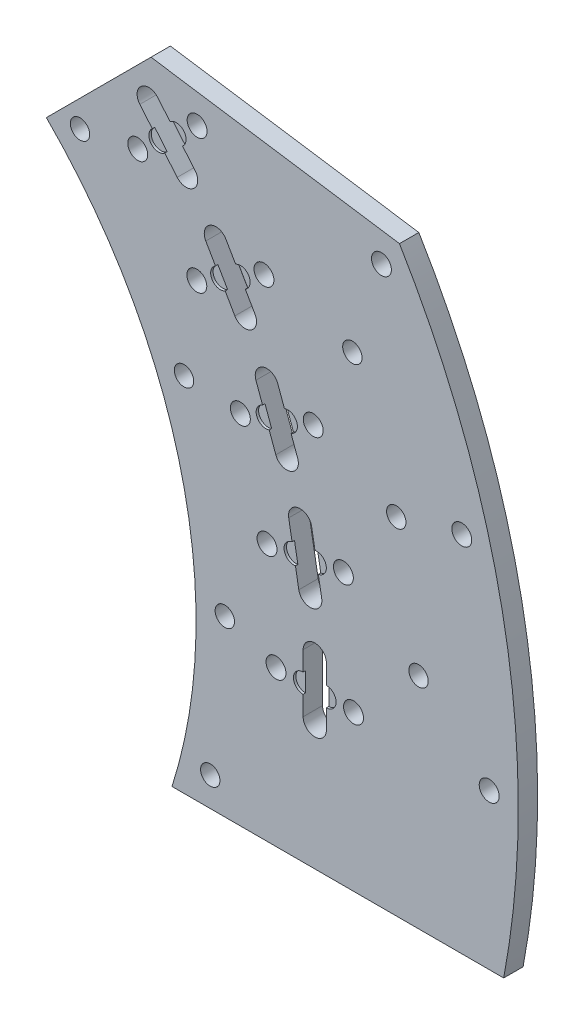
SolidWorks part; units mm, degrees
ref_plane "Front Plane" through (0, 0, 0) normal (0, 0, 1) x (1, 0, 0)
ref_plane "Top Plane" through (0, 0, 0) normal (0, 1, 0) x (1, 0, 0)
ref_plane "Right Plane" through (0, 0, 0) normal (1, 0, 0) x (0, 0, -1)
sketch "Sketch1" plane through (0, 0, 0) normal (0, 0, 1) x (1, 0, 0)
  line L0 (0, 0) -> (177.8, 0) construction
  line L1 (176.8984, 6.1774) -> (0, 0) construction
  line L2 (0, 0) -> (121.7947, 121.7947) construction
  line L3 (121.7947, 121.7947) -> (122.9173, 122.9173) construction
  line L4 (129.4542, 120.718) -> (0, 0) construction
  line L5 (0, 0) -> (163.5325, 67.7374) construction
  line L6 (167.4812, 0) -> (167.4812, -50.8) construction
  line L8 (159.5911, -50.8) -> (167.4812, -50.8) construction
  line L9 (172.1267, -41.275) -> (0, 0) construction
  line L10 (159.5911, -50.8) -> (268.2828, -50.8)
  line L11 (118.4271, 118.4271) -> (152.7152, 152.7152)
  line L12 (177.8, 0) -> (193.675, 0) construction
  line L13 (202.565, 0) -> (210.185, 0) construction
  line L14 (210.185, 0) -> (219.075, 0) construction
  line L15 (193.675, 0) -> (202.565, 0) construction
  line L16 (202.565, 0) -> (202.565, 9.525)
  line L17 (202.565, 0) -> (202.565, -9.525)
  line L18 (210.185, 9.525) -> (210.185, 0)
  line L19 (210.185, 0) -> (210.185, -9.525)
  line L20 (202.565, -9.525) -> (210.185, -9.525) construction
  line L21 (202.565, 9.525) -> (210.185, 9.525) construction
  line L22 (210.185, 9.525) -> (219.075, 0) construction
  line L23 (202.565, 9.525) -> (193.675, 0) construction
  line L24 (199.4876, 35.175) -> (201.1416, 25.7947)
  line L25 (199.4876, 35.175) -> (197.8336, 44.5553)
  line L26 (205.3378, 45.8785) -> (206.9918, 36.4982)
  line L27 (206.9918, 36.4982) -> (208.6458, 27.1179)
  line L28 (190.3488, 69.2813) -> (193.6066, 60.3307)
  line L29 (190.3488, 69.2813) -> (187.0911, 78.2319)
  line L30 (194.2516, 80.8381) -> (197.5093, 71.8875)
  line L31 (197.5093, 71.8875) -> (200.767, 62.9369)
  line L32 (175.4264, 101.2825) -> (180.1889, 93.0336)
  line L33 (175.4264, 101.2825) -> (170.6639, 109.5314)
  line L34 (177.263, 113.3414) -> (182.0255, 105.0925)
  line L35 (182.0255, 105.0925) -> (186.788, 96.8436)
  line L36 (155.1738, 130.2063) -> (161.2963, 122.9097)
  line L37 (155.1738, 130.2063) -> (149.0512, 137.5028)
  line L38 (154.8885, 142.4009) -> (161.0111, 135.1043)
  line L39 (161.0111, 135.1043) -> (167.1336, 127.8077)
  line L40 (0, 0) -> (193.675, 0) construction
  line L41 (0, 0) -> (190.7326, 33.6313) construction
  line L42 (0, 0) -> (254, 0) construction
  line L43 (254, 0) -> (263.525, 0) construction
  line L44 (254.5456, 68.2053) -> (0, 0) construction
  line L45 (152.7152, 152.7152) -> (234.123, 140.5088)
  line L46 (167.8212, 140.8187) -> (228.2193, 131.7625) construction
  line L47 (254.5456, 68.2053) -> (263.746, 70.6705) construction
  line L48 (0, 0) -> (240.3818, 21.0307) construction
  line L49 (0, 0) -> (240.3818, 21.0307) construction
  line L50 (0, 0) -> (233.0779, 62.453) construction
  arc A0 (172.2437, 0) -> (121.7947, 121.7947) centre (0, 0) ccw construction
  arc A1 (173.8312, 0) -> (122.9173, 122.9173) centre (0, 0) ccw construction
  circle A2 centre (176.8984, 6.1774) radius 3.175
  circle A3 centre (129.4542, 120.718) radius 3.175
  circle A4 centre (163.5325, 67.7374) radius 3.175
  arc A5 (167.4812, 0) -> (118.4271, 118.4271) centre (0, 0) ccw
  arc A6 (167.4812, 0) -> (159.5911, -50.8) centre (0, 0) cw
  arc A7 (173.8312, 0) -> (166.2428, -50.8) centre (0, 0) cw construction
  circle A8 centre (172.1267, -41.275) radius 3.175
  circle A9 centre (193.675, 0) radius 9.525 construction
  circle A10 centre (219.075, 0) radius 9.525 construction
  arc A11 (202.565, -9.525) -> (210.185, -9.525) centre (206.375, -9.525) ccw
  arc A12 (202.565, 9.525) -> (210.185, 9.525) centre (206.375, 9.525) cw
  circle A13 centre (193.675, 0) radius 3.2639
  circle A14 centre (219.075, 0) radius 3.2639
  circle A15 centre (215.7468, 38.042) radius 3.2639
  arc A16 (201.1416, 25.7947) -> (208.6458, 27.1179) centre (204.8937, 26.4563) ccw
  arc A17 (197.8336, 44.5553) -> (205.3378, 45.8785) centre (201.5857, 45.2169) cw
  circle A18 centre (190.7326, 33.6313) radius 3.2639
  circle A19 centre (205.8632, 74.9281) radius 3.2639
  arc A20 (193.6066, 60.3307) -> (200.767, 62.9369) centre (197.1868, 61.6338) ccw
  arc A21 (187.0911, 78.2319) -> (194.2516, 80.8381) centre (190.6713, 79.535) cw
  circle A22 centre (181.995, 66.2408) radius 3.2639
  circle A23 centre (189.7245, 109.5375) radius 3.2639
  arc A24 (180.1889, 93.0336) -> (186.788, 96.8436) centre (183.4885, 94.9386) ccw
  arc A25 (170.6639, 109.5314) -> (177.263, 113.3414) centre (173.9635, 111.4364) cw
  circle A26 centre (167.7275, 96.8375) radius 3.2639
  circle A27 centre (167.8212, 140.8187) radius 3.2639
  arc A28 (161.2963, 122.9097) -> (167.1336, 127.8077) centre (164.215, 125.3587) ccw
  arc A29 (149.0512, 137.5028) -> (154.8885, 142.4009) centre (151.9699, 139.9519) cw
  circle A30 centre (148.3637, 124.4919) radius 3.2639
  circle A31 centre (263.525, 0) radius 3.2639
  circle A32 centre (254.5456, 68.2053) radius 3.2639
  circle A33 centre (228.2193, 131.7625) radius 3.2639
  arc A34 (234.123, 140.5088) -> (268.2828, -50.8) centre (0, 0) cw
  circle A36 centre (240.3818, 21.0307) radius 3.175
  circle A37 centre (233.0779, 62.453) radius 3.175
  circle A38 centre (218.6921, 101.9778) radius 3.175
  point P3 (172.2437, 0)
  point P96 (0, 0)
  point P97 (223.9759, 105.0925)
  point P100 (-0.8179, 0)
  dimension "D3" = 1.5875
  dimension "D4" = 6.35
  dimension "D5" = 2
  dimension "D7" = 2
  dimension "D8" = 6.35
  dimension "D9" = 6.35
  dimension "D11" = 6.35
  dimension "D13" = 6.35
  dimension "D15" = 19.05
  dimension "D16" = 7.62
  dimension "D17" = 19.05
  dimension "D21" = 15.875
  dimension "D22" = 6.5278
  dimension "D23" = 6.5278
  dimension "D28" = 6.5278
  dimension "D32" = 9.525
  dimension "D33" = 5
  dimension "D34" = 241.3
  dimension "D35" = 6.35
  dimension "D1" = 177.8
  dimension "D2" = 5.5562
  dimension "D6" = 45
  dimension "D10" = 22.5
  dimension "D12" = 50.8
  dimension "D14" = 9.525
  dimension "D18" = 9.525
  dimension "D19" = 9.525
  dimension "D20" = 25.4
  dimension "D25" = 10
  dimension "D26" = 254
  dimension "D27" = 9.525
  dimension "D30" = 15
  dimension "D31" = 9.525
  dimension "D37" = 10
  dimension "D24" = 5
  dimension "D29" = 3
  dimension "D36" = 3
extrude "Boss-Extrude1" add sketch "Sketch1" along normal blind 6.35 contours A34 L45 L11 A5 A6 L10 A33 A32 A31 A30 A27 A26 A23 A22 A19 A18 A15 A14 A13 A8 A4 A3 A2 L16 A12 L18 L19 A11 L17 L25 A17 L26
sketch "Sketch2" plane through (0, 0, 6.35) normal (0, 0, 1) x (1, 0, 0)
  line L0 (202.565, -9.525) -> (202.565, 9.525) construction
  line L1 (210.185, 9.525) -> (210.185, -9.525) construction
  line L2 (0, 0) -> (202.565, 0) construction
  line L3 (0, 0) -> (199.4876, 35.175) construction
  circle A0 centre (202.565, 0) radius 3.175
  circle A1 centre (210.185, 0) radius 3.175
  circle A2 centre (199.4876, 35.175) radius 3.175
  circle A3 centre (206.9918, 36.4982) radius 3.175
  circle A4 centre (190.3488, 69.2813) radius 3.175
  circle A5 centre (197.5093, 71.8875) radius 3.175
  circle A6 centre (175.4264, 101.2825) radius 3.175
  circle A7 centre (182.0255, 105.0925) radius 3.175
  circle A8 centre (155.1738, 130.2063) radius 3.175
  circle A9 centre (161.0111, 135.1043) radius 3.175
  dimension "D1" = 6.35
  dimension "D2" = 6.35
  dimension "D4" = 10
  dimension "D3" = 5
extrude "Cut-Extrude1" cut sketch "Sketch2" against normal blind 0.7937
